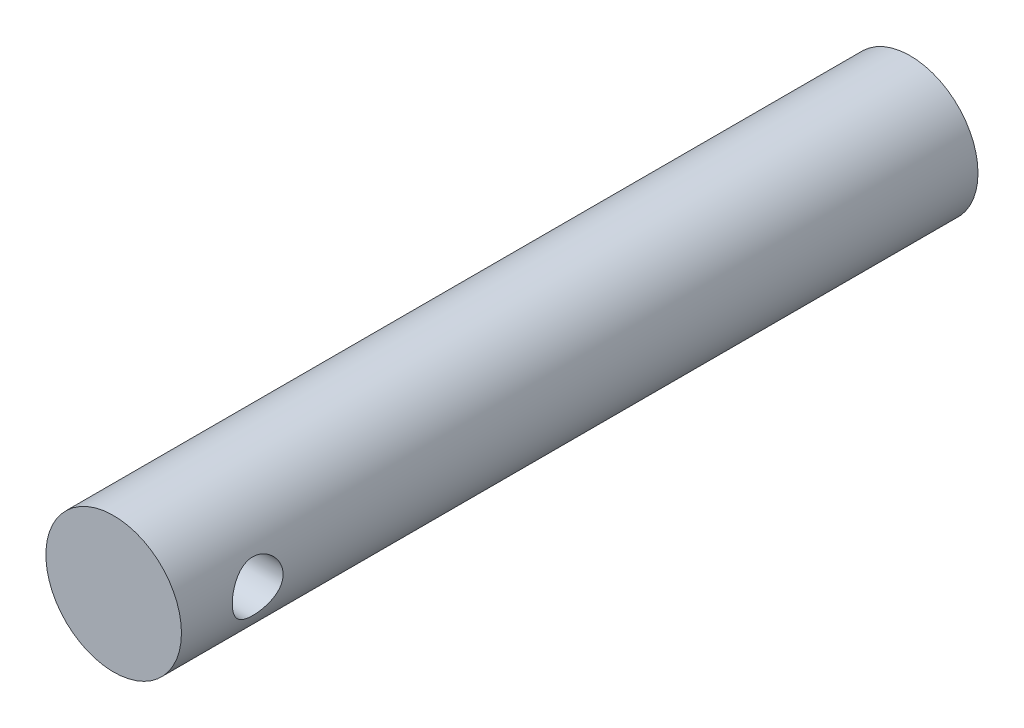
SolidWorks part; units mm, degrees
material "AISI 304"
ref_plane "Front" through (0, 0, 0) normal (0, 0, 1) x (1, 0, 0)
ref_plane "Top" through (0, 0, 0) normal (0, 1, 0) x (1, 0, 0)
ref_plane "Right" through (0, 0, 0) normal (1, 0, 0) x (0, 0, -1)
sketch "Sketch1" plane through (0, 0, 0) normal (0, 0, 1) x (1, 0, 0)
  circle A0 centre (0, 0) radius 4
  dimension "D1" = 8
extrude "Boss-Extrude1" add sketch "Sketch1" along normal blind 47
ref_plane "Plane1" through (4, 0, 0) normal (1, 0, 0) x (0, 0, -1)
sketch "Sketch2" plane through (4, 0, 0) normal (1, 0, 0) x (0, 0, -1)
  line L0 (-47, 4) -> (-47, -4) construction
  circle A0 centre (-42.5, 0) radius 1.5
  dimension "D1" = 3
  dimension "D2" = 4.5
extrude "Cut-Extrude1" cut sketch "Sketch2" against normal through all
